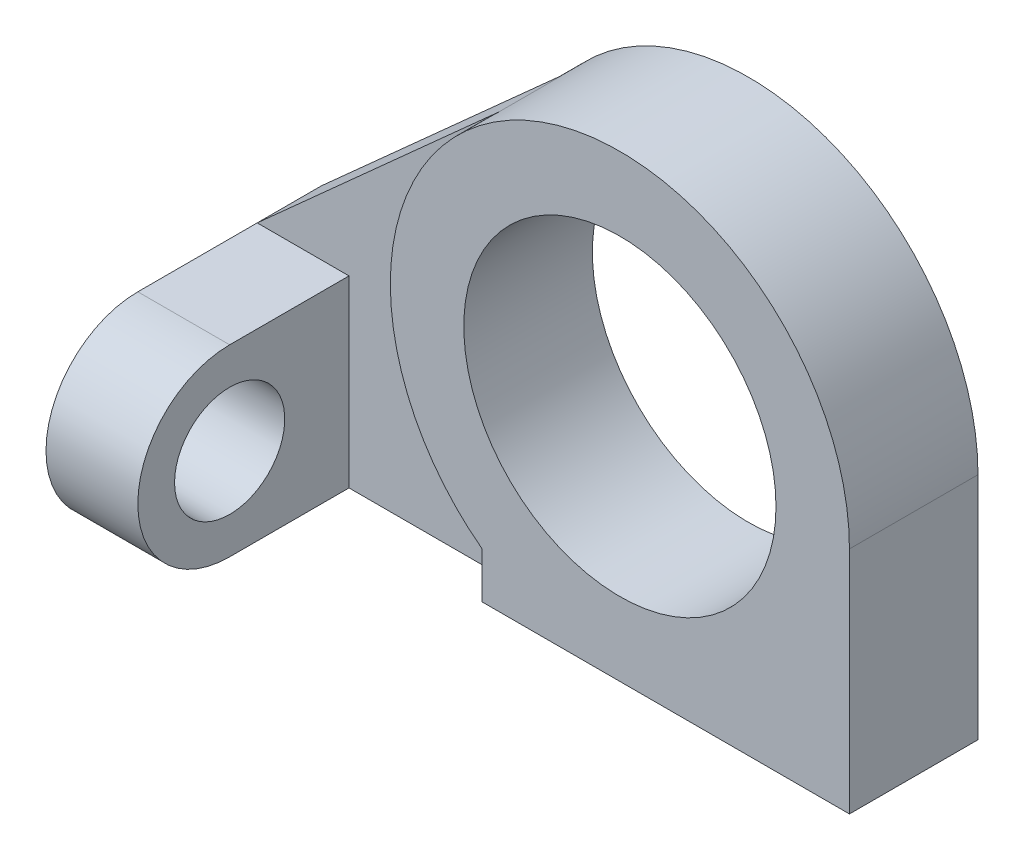
SolidWorks part; units mm, degrees
ref_plane "Ön Düzlem" through (0, 0, 0) normal (0, 0, 1) x (1, 0, 0)
ref_plane "Üst Düzlem" through (0, 0, 0) normal (0, 1, 0) x (1, 0, 0)
ref_plane "Sağ Düzlem" through (0, 0, 0) normal (1, 0, 0) x (0, 0, -1)
sketch "Sketch1" plane through (0, 0, 0) normal (0, 0, 1) x (1, 0, 0)
  line L0 (25, 0) -> (25, -25)
  line L1 (25, -25) -> (-47, -25)
  line L2 (-47, -25) -> (-47, -9)
  line L3 (-47, -9) -> (-43, -9)
  line L4 (-43, -9) -> (-43, -5)
  line L5 (-43, -5) -> (-16.6983, 18.6055)
  circle A0 centre (0, 0) radius 17
  arc A1 (25, 0) -> (-16.6983, 18.6055) centre (0, 0) ccw
  point P3 (0, 0)
  point P12 (0, 0)
  point P13 (25.7419, -25)
  dimension "D1" = 34
  dimension "D2" = 50
  dimension "D3" = 25
  dimension "D4" = 72
  dimension "D5" = 16
  dimension "D6" = 4
  dimension "D7" = 4
extrude "Boss-Extrude1" add sketch "Sketch1" along normal mid plane 7
sketch "Sketch3" plane through (0, 0, 3.5) normal (0, 0, 1) x (1, 0, 0)
  line L0 (25, -25) -> (25, 0) construction
  line L1 (-47, -25) -> (25, -25) construction
  line L2 (25, -25) -> (25, 0)
  line L3 (-15, -25) -> (25, -25)
  line L4 (-15, -25) -> (-15, -20)
  circle A0 centre (0, 0) radius 17 construction
  circle A1 centre (0, 0) radius 17
  arc A2 (25, 0) -> (-15, -20) centre (0, 0) ccw
  dimension "D1" = 40
extrude "Boss-Extrude2" add sketch "Sketch3" along normal blind 3.5
mirror "Mirror1" about plane through (0, 0, 0) normal (0, 0, 1) of "Boss-Extrude2"
sketch "Sketch4" plane through (-43, 0, 0) normal (-1, 0, 0) x (0, 0, 1)
  line L1 (3.5, -5) -> (16.5, -5)
  line L2 (3.5, -5) -> (3.5, -25)
  line L3 (3.5, -25) -> (16.5, -25)
  circle A0 centre (16.5, -15) radius 6
  arc A1 (16.5, -25) -> (16.5, -5) centre (16.5, -15) ccw
  dimension "D3" = 12
  dimension "D4" = 10
  dimension "D1" = 20
  dimension "D2" = 13
extrude "Boss-Extrude3" add sketch "Sketch4" against normal blind 10
